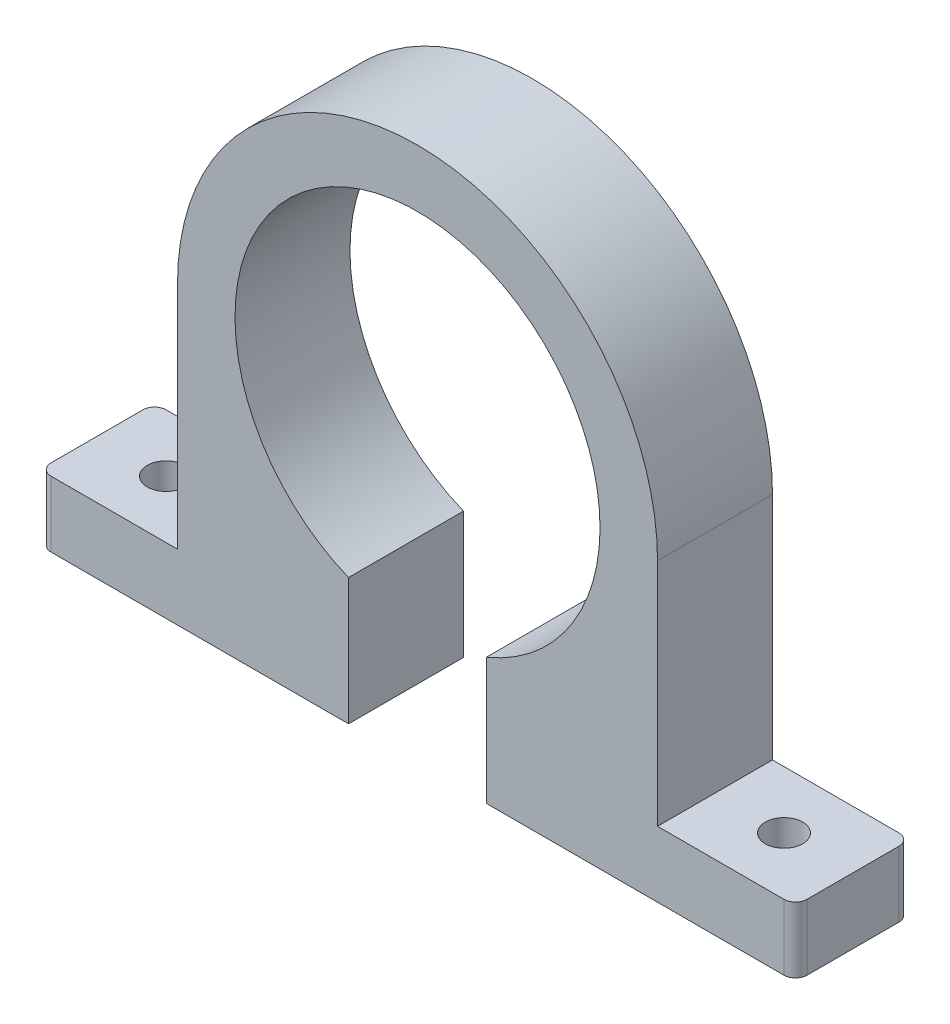
SolidWorks part; units mm, degrees
material "Delrin 2700 NC010, Low Viscosity Acetal Copolymer (SS)"
ref_plane "Front Plane" through (0, 0, 0) normal (0, 0, 1) x (1, 0, 0)
ref_plane "Top Plane" through (0, 0, 0) normal (0, 1, 0) x (1, 0, 0)
ref_plane "Right Plane" through (0, 0, 0) normal (1, 0, 0) x (0, 0, -1)
sketch "Sketch1" plane through (0, 0, 0) normal (0, 0, 1) x (1, 0, 0)
  line L0 (-20.875, 0) -> (-20.875, -20)
  line L1 (-20.875, -20) -> (-32.875, -20)
  line L2 (-32.875, -20) -> (-32.875, -25.72)
  line L3 (-32.875, -25.72) -> (-6, -25.72)
  line L4 (32.875, -25.72) -> (32.875, -20)
  line L5 (32.875, -20) -> (20.875, -20)
  line L6 (20.875, -20) -> (20.875, 0)
  line L7 (-6, -25.72) -> (-6, -14.6975)
  line L8 (6, -25.72) -> (6, -14.6975)
  line L9 (6, -25.72) -> (32.875, -25.72)
  arc A0 (6, -14.6975) -> (-6, -14.6975) centre (0, 0) ccw
  arc A1 (20.875, 0) -> (-20.875, 0) centre (0, 0) ccw
  dimension "D1" = 31.75
  dimension "D2" = 41.75
  dimension "D3" = 20
  dimension "D5" = 12
  dimension "D4" = 25.72
  dimension "D6" = 6
  dimension "D7" = 6
extrude "Boss-Extrude1" add sketch "Sketch1" along normal blind 10
fillet "Fillet1" radius 1 4 edges at (32.875, -22.86, 0) (32.875, -22.86, 10) (-32.875, -22.86, 0) (-32.875, -22.86, 10)
hole_wizard "#4 Clearance Hole1" positions "Sketch2" profile "Sketch3" hole size "#4" standard "ANSI Inch" end condition through all
sketch "Sketch2" plane through (0, -20, 0) normal (0, 1, 0) x (1, 0, 0)
  line L0 (-32.875, -9) -> (-32.875, -1) construction
  line L3 (32.875, -9) -> (32.875, -1) construction
  point P0 (-26.875, -5)
  point P2 (26.875, -5)
  point P8 (-32.875, -5)
  dimension "D1" = 6
  dimension "D2" = 6
sketch "Sketch3" plane through (-26.875, -20, 5) normal (1, 0, 0) x (0, 0, 1)
  line L0 (0, 0) -> (0, 5.72)
  line L1 (0, 5.72) -> (1.6319, 5.72)
  line L2 (1.6319, 5.72) -> (1.6319, 0)
  line L5 (1.6319, 0) -> (0, 0)
  line L11 (0, -6.35) -> (0, 107.95) construction
  dimension "Thru Hole Dia." = 3.2639
  dimension "Thru Hole Depth" = 5.72
equation "\"D2@Sketch1\"=\"D1@Sketch1\"+(2*5)"
equation "\"D2@Sketch2\"=\"D1@Sketch2\""
equation "\"D6@Sketch1\"=\"D7@Sketch1\""
